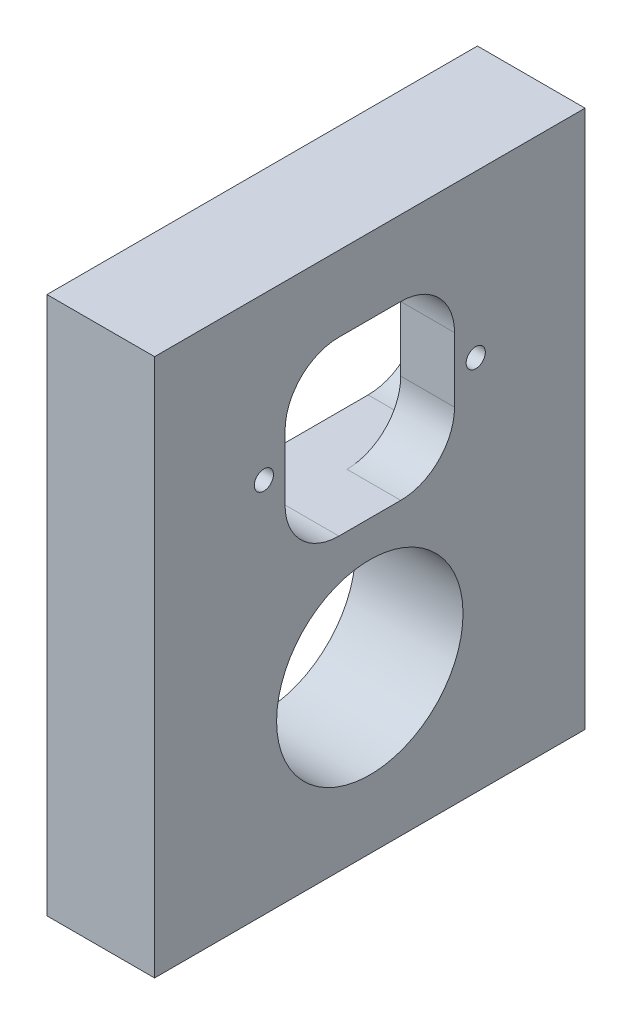
SolidWorks part; units mm, degrees
ref_plane "Front Plane" through (0, 0, 0) normal (0, 0, 1) x (1, 0, 0)
ref_plane "Top Plane" through (0, 0, 0) normal (0, 1, 0) x (1, 0, 0)
ref_plane "Right Plane" through (0, 0, 0) normal (1, 0, 0) x (0, 0, -1)
sketch "Sketch1" plane through (0, 0, 0) normal (1, 0, 0) x (0, 0, -1)
  line L1 (-25.4, -31.75) -> (25.4, -31.75)
  line L2 (-25.4, -31.75) -> (-25.4, 31.75)
  line L3 (-25.4, 31.75) -> (25.4, 31.75)
  line L4 (25.4, -31.75) -> (25.4, 31.75)
  line L5 (-25.4, -31.75) -> (25.4, 31.75) construction
  line L6 (-25.4, 31.75) -> (25.4, -31.75) construction
  point P0 (0, 0)
  dimension "D1" = 50.8
  dimension "D2" = 63.5
extrude "Boss-Extrude1" add sketch "Sketch1" along normal blind 12.7
hole_wizard "Ø22.0 (22) Diameter Hole1" positions "Sketch3" profile "Sketch2" hole size "Ø22.0" standard "ANSI Metric" end condition through all
sketch "Sketch3" plane through (12.7, 0, 0) normal (1, 0, 0) x (0, 0, -1)
  line L1 (25.4, 31.75) -> (-25.4, 31.75) construction
  line L2 (0, -31.75) -> (0, 31.75) construction
  line L3 (-25.4, -31.75) -> (25.4, -31.75) construction
  point P0 (0, -12.7)
  dimension "D1" = 44.45
sketch "Sketch2" plane through (12.7, -12.7, 0) normal (0, 1, 0) x (0, 0, -1)
  line L0 (0, 0) -> (0, 12.7)
  line L1 (0, 12.7) -> (11, 12.7)
  line L2 (11, 12.7) -> (11, 0)
  line L5 (11, 0) -> (0, 0)
  line L11 (0, -6.35) -> (0, 107.95) construction
  dimension "Thru Hole Dia." = 22
  dimension "Thru Hole Depth" = 12.7
hole_wizard "1/16 NPT Tapped Hole1" positions "Sketch5" profile "Sketch4" size "1/16" standard "ANSI Inch"
sketch "Sketch5" plane through (0, 0, 0) normal (-1, 0, 0) x (0, 0, 1)
  line L0 (25.4, -31.75) -> (-25.4, -31.75) construction
  circle A0 centre (0, -12.7) radius 11 construction
  point P0 (0, 12.7)
  point P5 (0, -31.75)
  dimension "D1" = 25.4
  dimension "D2" = 0
sketch "Sketch4" plane through (0, 12.7, 0) normal (0, 1, 0) x (0, 0, 1)
  line L0 (0, 0) -> (0, 13.5307)
  line L1 (3.0734, 11.684) -> (0, 13.5307)
  line L2 (-3.0734, 11.684) -> (0, 13.5307) construction
  line L3 (3.0734, 11.684) -> (3.0734, 6.858)
  line L4 (3.0734, 6.858) -> (3.7626, 6.858)
  line L5 (3.7626, 6.858) -> (3.9679, 0)
  line L6 (-3.7626, 6.858) -> (-3.9679, 0) construction
  line L7 (3.9679, 0) -> (0, 0)
  line L8 (0, -6.35) -> (0, 107.95) construction
  line L11 (-3.0734, 6.858) -> (-3.7626, 6.858) construction
  dimension "Tap Drill Dia." = 6.1468
  dimension "Tap Drill Depth" = 11.684
  dimension "Thread Dia." = 7.9358
  dimension "Thread Angle" = 3.43
  dimension "Thread Depth" = 6.858
  dimension "Drill Angle" = 118
hole_wizard "#4-40 Tapped Hole1" positions "Sketch7" profile "Sketch6" tap size "#4-40" standard "ANSI Inch" end condition through all
sketch "Sketch7" plane through (12.7, 0, 0) normal (1, 0, 0) x (0, 0, -1)
  line L0 (35.4085, 12.7) -> (-36.5694, 12.7) construction
  line L1 (0, 23.5312) -> (0, 12.7) construction
  circle A1 centre (0, 12.7) radius 3.5877 construction
  circle A2 centre (0, 12.7) radius 3.5877
  point P0 (-12.5, 12.7)
  point P2 (12.5, 12.7)
  dimension "D1" = 25
sketch "Sketch6" plane through (12.7, 12.7, 12.5) normal (0, 1, 0) x (0, 0, -1)
  line L0 (0, 0) -> (0, 12.7)
  line L1 (0, 12.7) -> (1.1303, 12.7)
  line L2 (1.1303, 12.7) -> (1.1303, 0)
  line L5 (1.1303, 0) -> (0, 0)
  line L11 (0, -6.35) -> (0, 107.95) construction
  dimension "Thread Major Dia." = 2.2606
  dimension "Thru Tap Drill Depth" = 12.7
sketch "Sketch9" plane through (12.7, 0, 0) normal (1, 0, 0) x (0, 0, -1)
  line L1 (-3.65, 2.54) -> (3.65, 2.54)
  line L2 (-10, 8.89) -> (-10, 16.51)
  line L3 (-3.65, 22.86) -> (3.65, 22.86)
  line L4 (10, 8.89) -> (10, 16.51)
  line L5 (-10, 2.54) -> (10, 22.86) construction
  line L6 (-10, 22.86) -> (10, 2.54) construction
  arc A0 (3.65, 22.86) -> (10, 16.51) centre (3.65, 16.51) cw
  arc A1 (3.65, 2.54) -> (10, 8.89) centre (3.65, 8.89) ccw
  arc A2 (-10, 8.89) -> (-3.65, 2.54) centre (-3.65, 8.89) ccw
  arc A3 (-3.65, 22.86) -> (-10, 16.51) centre (-3.65, 16.51) ccw
  point P0 (0, 12.7)
  dimension "D1" = 6.35
  dimension "D2" = 10
  dimension "D3" = 10.16
extrude "Cut-Extrude1" cut sketch "Sketch9" against normal through all
sketch "Sketch10" plane through (0, 0, 0) normal (1, 0, 0) x (0, 0, -1)
  line L0 (-11.3697, 12.7) -> (25.4, 12.7) construction
  line L1 (-12.5, 2.54) -> (12.5, 2.54)
  line L2 (-18.85, 8.89) -> (-18.85, 16.51)
  line L3 (-12.5, 22.86) -> (12.5, 22.86)
  line L4 (18.85, 8.89) -> (18.85, 16.51)
  line L5 (-18.85, 2.54) -> (18.85, 22.86) construction
  line L6 (-18.85, 22.86) -> (18.85, 2.54) construction
  line L7 (25.4, -31.75) -> (25.4, 31.75) construction
  line L8 (0, -23.7) -> (0, 31.75) construction
  line L9 (25.4, 31.75) -> (-25.4, 31.75) construction
  circle A0 centre (-12.5, 12.7) radius 1.1303 construction
  circle A1 centre (0, -12.7) radius 11 construction
  arc A2 (12.5, 22.86) -> (18.85, 16.51) centre (12.5, 16.51) cw
  arc A3 (12.5, 2.54) -> (18.85, 8.89) centre (12.5, 8.89) ccw
  arc A4 (-12.5, 2.54) -> (-18.85, 8.89) centre (-12.5, 8.89) cw
  arc A5 (-18.85, 16.51) -> (-12.5, 22.86) centre (-12.5, 16.51) cw
  point P0 (0, 12.7)
  dimension "D1" = 6.35
  dimension "D3" = 6.35
  dimension "D2" = 10.16
extrude "Cut-Extrude2" cut sketch "Sketch10" along normal blind 6.35
